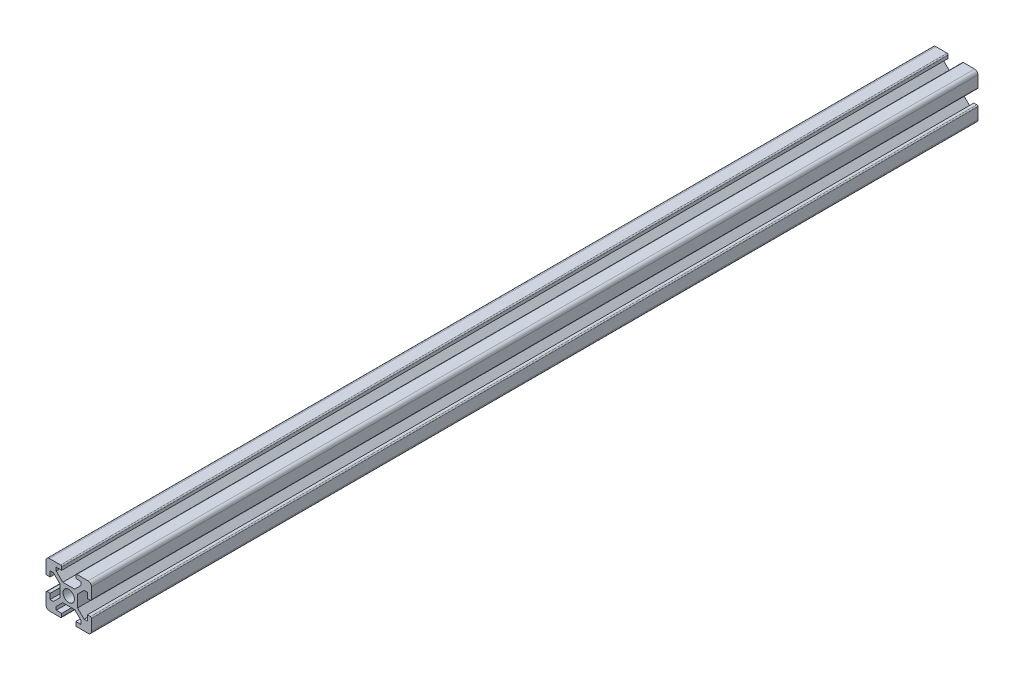
SolidWorks part; units mm, degrees
ref_plane "前视基准面" through (0, 0, 0) normal (0, 0, 1) x (1, 0, 0)
ref_plane "上视基准面" through (0, 0, 0) normal (0, 1, 0) x (1, 0, 0)
ref_plane "右视基准面" through (0, 0, 0) normal (1, 0, 0) x (0, 0, -1)
sketch "草图1" plane through (0, 0, 0) normal (0, 0, 1) x (1, 0, 0)
  line L0 (0, 6.9) -> (0, 0)
  line L1 (20, 20) -> (20, 13.1)
  line L2 (1.8, 15.5) -> (3.2272, 15.5)
  line L3 (4.5, 16.7728) -> (4.5, 18.2)
  line L4 (0, 13.1) -> (0, 20)
  line L5 (6.9, 20) -> (6.9, 18.2)
  line L6 (6.9, 18.2) -> (4.5, 18.2)
  line L7 (13.1, 20) -> (20, 20)
  line L8 (6.9, 20) -> (0, 20)
  line L9 (0, 0) -> (6.9, 0)
  line L10 (13.1, 0) -> (20, 0)
  line L11 (15.5, 18.2) -> (15.5, 16.7728)
  line L12 (16.7728, 15.5) -> (18.2, 15.5)
  line L13 (20, 6.9) -> (20, 0)
  line L14 (1.8, 4.5) -> (3.2272, 4.5)
  line L15 (4.5, 3.2272) -> (4.5, 1.8)
  line L16 (12.6272, 6.1) -> (15.5, 3.2272)
  line L17 (18.2, 4.5) -> (16.7728, 4.5)
  line L18 (15.5, 3.2272) -> (15.5, 1.8)
  line L19 (13.9, 7.3728) -> (16.7728, 4.5)
  line L20 (13.1, 20) -> (13.1, 18.2)
  line L21 (13.1, 18.2) -> (15.5, 18.2)
  line L22 (7.3728, 13.9) -> (12.6272, 13.9)
  line L23 (13.9, 12.6272) -> (13.9, 7.3728)
  line L24 (7.3728, 6.1) -> (12.6272, 6.1)
  line L25 (6.1, 12.6272) -> (6.1, 7.3728)
  line L27 (12.6272, 13.9) -> (15.5, 16.7728)
  line L30 (3.2272, 4.5) -> (6.1, 7.3728)
  line L32 (4.5, 3.2272) -> (7.3728, 6.1)
  line L33 (20, 13.1) -> (18.2, 13.1)
  line L34 (18.2, 13.1) -> (18.2, 15.5)
  line L36 (20, 6.9) -> (18.2, 6.9)
  line L37 (18.2, 6.9) -> (18.2, 4.5)
  line L39 (13.1, 0) -> (13.1, 1.8)
  line L40 (13.1, 1.8) -> (15.5, 1.8)
  line L42 (6.9, 0) -> (6.9, 1.8)
  line L43 (6.9, 1.8) -> (4.5, 1.8)
  line L45 (0, 6.9) -> (1.8, 6.9)
  line L46 (1.8, 6.9) -> (1.8, 4.5)
  line L48 (0, 13.1) -> (1.8, 13.1)
  line L49 (1.8, 13.1) -> (1.8, 15.5)
  line L50 (4.5, 16.7728) -> (7.3728, 13.9)
  line L51 (3.2272, 15.5) -> (6.1, 12.6272)
  line L53 (13.9, 12.6272) -> (16.7728, 15.5)
  line L62 (1.8, 13.1) -> (1.8, 15.5)
  line L63 (0, 13.1) -> (1.8, 13.1)
  line L66 (6.9, 18.2) -> (4.5, 18.2)
  line L67 (6.9, 20) -> (6.9, 18.2)
  line L68 (3.2272, 15.5) -> (1.8, 15.5)
  line L69 (4.5, 18.2) -> (4.5, 16.7728)
  line L75 (4.5, 1.8) -> (4.5, 3.2272)
  line L76 (3.2272, 4.5) -> (1.8, 4.5)
  line L77 (6.9, 0) -> (6.9, 1.8)
  line L78 (6.9, 1.8) -> (4.5, 1.8)
  line L80 (0, 6.9) -> (1.8, 6.9)
  line L81 (1.8, 6.9) -> (1.8, 4.5)
  line L90 (1.8, 6.9) -> (1.8, 4.5)
  line L91 (0, 6.9) -> (1.8, 6.9)
  line L93 (18.2, 6.9) -> (18.2, 4.5)
  line L94 (20, 6.9) -> (18.2, 6.9)
  line L98 (13.1, 1.8) -> (15.5, 1.8)
  line L99 (13.1, 0) -> (13.1, 1.8)
  line L100 (16.7728, 4.5) -> (18.2, 4.5)
  line L101 (15.5, 1.8) -> (15.5, 3.2272)
  line L106 (6.9, 1.8) -> (4.5, 1.8)
  line L107 (6.9, 0) -> (6.9, 1.8)
  line L109 (4.5, 3.2272) -> (4.5, 1.8)
  line L110 (1.8, 4.5) -> (3.2272, 4.5)
  circle A0 centre (10, 10) radius 2.5
extrude "凸台-拉伸1" add sketch "草图1" along normal blind 390 contours L23 L53 L12 L34 L33 L1 L7 L20 L21 L11 L27 L22 L50 L3 L6 L5 L8 L4 L48 L49 L2 L51 L25 L30 L14 L46 L45 L0 L9 L42 L43 L15 L32 L24 L16 L18 L40 L39 L10 L13 L36 L37 L17 L19
fillet "圆角1" radius 1.5 1 edges at (20, 20, 195)
fillet "圆角2" radius 1.5 1 edges at (0, 20, 195)
fillet "圆角3" radius 1.5 1 edges at (0, 0, 195)
fillet "圆角4" radius 1.5 1 edges at (20, 0, 195)
fillet "圆角5" radius 0.5 1 edges at (13.1, 20, 195)
fillet "圆角6" radius 0.5 1 edges at (6.9, 20, 195)
fillet "圆角7" radius 0.5 1 edges at (0, 13.1, 195)
fillet "圆角8" radius 0.5 1 edges at (0, 6.9, 195)
fillet "圆角9" radius 0.5 1 edges at (6.9, 0, 195)
fillet "圆角10" radius 0.5 1 edges at (13.1, 0, 195)
fillet "圆角11" radius 0.5 1 edges at (20, 13.1, 195)
fillet "圆角12" radius 0.5 1 edges at (20, 6.9, 195)
